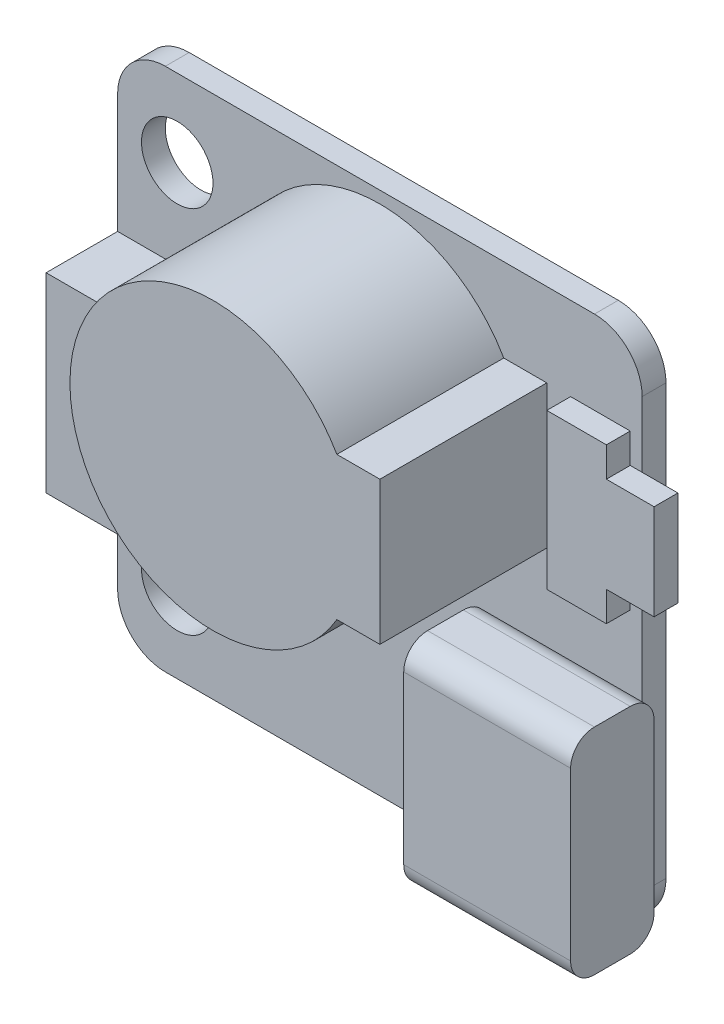
SolidWorks part; units mm, degrees
ref_plane "Front Plane" through (0, 0, 0) normal (1, 0, 0) x (0, 1, 0)
ref_plane "Top Plane" through (0, 0, 0) normal (0, 0, 1) x (0, 1, 0)
ref_plane "Right Plane" through (0, 0, 0) normal (0, 1, 0) x (-1, 0, 0)
sketch "Sketch1" plane through (0, 0, 0) normal (0, 0, 1) x (0, 1, 0)
  line L0 (-7.75, 8.5) -> (7.75, 8.5) construction
  line L1 (-9, 11) -> (9, 11)
  line L2 (-11, 9) -> (-11, -9)
  line L3 (-9, -11) -> (9, -11)
  line L4 (11, 9) -> (11, -9)
  line L5 (-11, 11) -> (11, -11) construction
  line L6 (-11, -11) -> (11, 11) construction
  arc A0 (-11, -9) -> (-9, -11) centre (-9, -9) ccw
  arc A1 (9, -11) -> (11, -9) centre (9, -9) ccw
  arc A2 (9, 11) -> (11, 9) centre (9, 9) cw
  arc A3 (-9, 11) -> (-11, 9) centre (-9, 9) ccw
  circle A6 centre (-7.75, 8.5) radius 1.5
  circle A7 centre (7.75, 8.5) radius 1.5
  point P0 (0, 0)
  point P19 (0, 8.5)
  point P20 (0, 0)
  point P22 (-7.75, 10)
  point P26 (29.6461, -1.0434)
  dimension "D2" = 2
  dimension "D3" = 15.5
  dimension "D5" = 3
  dimension "D1" = 22
  dimension "D4" = 1
extrude "Boss-Extrude1" add sketch "Sketch1" along normal blind 1
sketch "Sketch2" plane through (0, 0, 1) normal (0, 0, 1) x (1, 0, 0)
  line L0 (-11, 9) -> (-11, -9) construction
  line L1 (-11, 4) -> (-6.5, 4)
  line L2 (-11, 4) -> (-11, -4)
  line L3 (-11, -4) -> (-6.5, -4)
  line L4 (-6.5, 4) -> (-6.5, -4)
  point P6 (-6.5, 0)
  dimension "D1" = 4.5
  dimension "D2" = 8
extrude "Boss-Extrude2" add sketch "Sketch2" along normal blind 3
sketch "Sketch3" plane through (0, 0, 1) normal (0, 0, 1) x (1, 0, 0)
  line L1 (7, 7.5) -> (5.1962, 7.5)
  line L2 (7, 7.5) -> (7, 1.5)
  line L3 (7, 1.5) -> (5.1962, 1.5)
  line L5 (7, 7.5) -> (5.1962, 1.5) construction
  line L6 (7, 1.5) -> (5.1962, 7.5) construction
  arc A0 (5.1962, 7.5) -> (5.1962, 1.5) centre (0, 4.5) ccw
  point P2 (6.0981, 4.5)
  dimension "D2" = 12
  dimension "D1" = 7
  dimension "D3" = 4.5
  dimension "D4" = 6
extrude "Boss-Extrude3" add sketch "Sketch3" along normal blind 7
sketch "Sketch4" plane through (11, 0, 0) normal (1, 0, 0) x (0, 1, 0)
  line L0 (-8.75, 2.75) -> (-3.25, 2.75) construction
  line L1 (-8.75, 4.5) -> (-3.25, 4.5) construction
  line L2 (-8.75, 1) -> (-3.25, 1) construction
  line L3 (-9, 1) -> (9, 1) construction
  line L5 (-9, 0) -> (9, 0) construction
  line L6 (11, 1) -> (9, 1) construction
  line L7 (-9.5, 4.5) -> (-2.5, 4.5)
  line L8 (-10.5, 3.5) -> (-10.5, 2)
  line L9 (-9.5, 1) -> (-2.5, 1)
  line L10 (-1.5, 3.5) -> (-1.5, 2)
  line L11 (-10.5, 4.5) -> (-1.5, 1) construction
  line L12 (-10.5, 1) -> (-1.5, 4.5) construction
  line L13 (-11, 1) -> (-11, 0) construction
  arc A0 (-8.75, 4.5) -> (-8.75, 1) centre (-8.75, 2.75) ccw construction
  arc A1 (-3.25, 1) -> (-3.25, 4.5) centre (-3.25, 2.75) ccw construction
  arc A2 (-10.5, 2) -> (-9.5, 1) centre (-9.5, 2) ccw
  arc A3 (-2.5, 1) -> (-1.5, 2) centre (-2.5, 2) ccw
  arc A4 (-2.5, 4.5) -> (-1.5, 3.5) centre (-2.5, 3.5) cw
  arc A5 (-9.5, 4.5) -> (-10.5, 3.5) centre (-9.5, 3.5) ccw
  point P2 (-6, 2.75)
  point P9 (-10.5, 2.75)
  point P10 (-1.5, 2.75)
  point P11 (-6, 2.75)
  dimension "D1" = 0.5
  dimension "D4" = 1
  dimension "D2" = 9
  dimension "D3" = 4.5
extrude "Boss-Extrude4" add sketch "Sketch4" along normal blind 0.5 and the other way blind 6.5
sketch "Sketch5" plane through (0, 0, 1) normal (0, 0, 1) x (1, 0, 0)
  line L0 (11, -2.5) -> (11, 9) construction
  line L1 (8, 7.5) -> (10.5, 7.5)
  line L2 (8, 7.5) -> (8, 1)
  line L3 (8, 1) -> (10.5, 1)
  line L4 (10.5, 7.5) -> (10.5, 1)
  line L5 (8, 7.5) -> (10.5, 1) construction
  line L6 (8, 1) -> (10.5, 7.5) construction
  line L9 (9, 11) -> (-9, 11) construction
  line L10 (12.5, 2.25) -> (10.5, 2.25)
  line L11 (12.5, 2.25) -> (12.5, 6.25)
  line L12 (12.5, 6.25) -> (10.5, 6.25)
  line L13 (10.5, 2.25) -> (10.5, 6.25)
  line L14 (12.5, 2.25) -> (10.5, 6.25) construction
  line L15 (12.5, 6.25) -> (10.5, 2.25) construction
  point P0 (9.25, 4.25)
  point P10 (11.5, 4.25)
  line M28 (11, -2.5) -> (11, 9)
  dimension "D1" = 0.5
  dimension "D2" = 2.5
  dimension "D3" = 6.5
  dimension "D4" = 3.5
  dimension "D5" = 4
  dimension "D6" = 2
extrude "Boss-Extrude5" add sketch "Sketch5" along normal blind 1 contours L4 L1 L2 L3 | L11 L12 L10 M28
